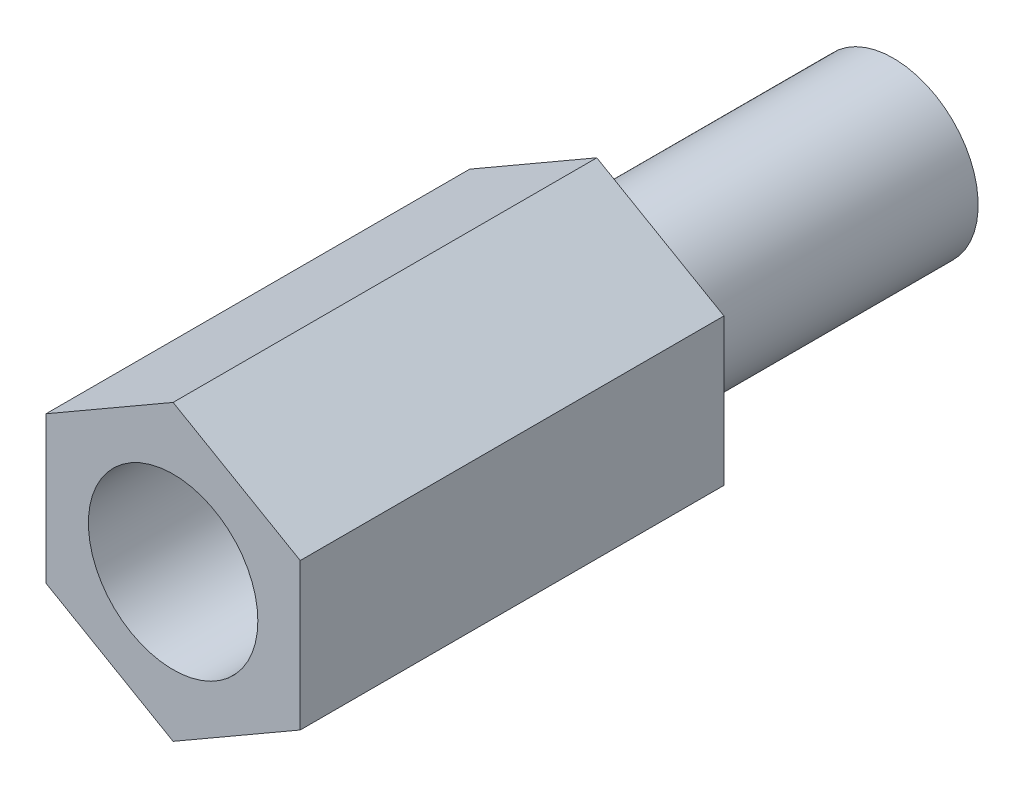
SolidWorks part; units mm, degrees
material "铜"
ref_plane "前视基准面" through (0, 0, 0) normal (0, 0, 1) x (1, 0, 0)
ref_plane "上视基准面" through (0, 0, 0) normal (0, 1, 0) x (1, 0, 0)
ref_plane "右视基准面" through (0, 0, 0) normal (1, 0, 0) x (0, 0, -1)
sketch "草图1" plane through (0, 0, 0) normal (0, 0, 1) x (1, 0, 0)
  line L1 (0, -3.4641) -> (3, -1.7321)
  line L2 (3, -1.7321) -> (3, 1.7321)
  line L3 (3, 1.7321) -> (0, 3.4641)
  line L4 (0, 3.4641) -> (-3, 1.7321)
  line L5 (-3, 1.7321) -> (-3, -1.7321)
  line L6 (-3, -1.7321) -> (0, -3.4641)
  circle A0 centre (0, 0) radius 3 construction
extrude "凸台-拉伸1" add sketch "草图1" along normal blind 10
sketch "草图2" plane through (0, 0, 10) normal (0, 0, 1) x (1, 0, 0)
  circle A0 centre (0, 0) radius 2
extrude "切除-拉伸1" cut sketch "草图2" against normal blind 4
sketch "草图3" plane through (0, 0, 0) normal (0, 0, -1) x (-1, 0, 0)
  circle A0 centre (0, 0) radius 2
extrude "凸台-拉伸2" add sketch "草图3" along normal blind 7
